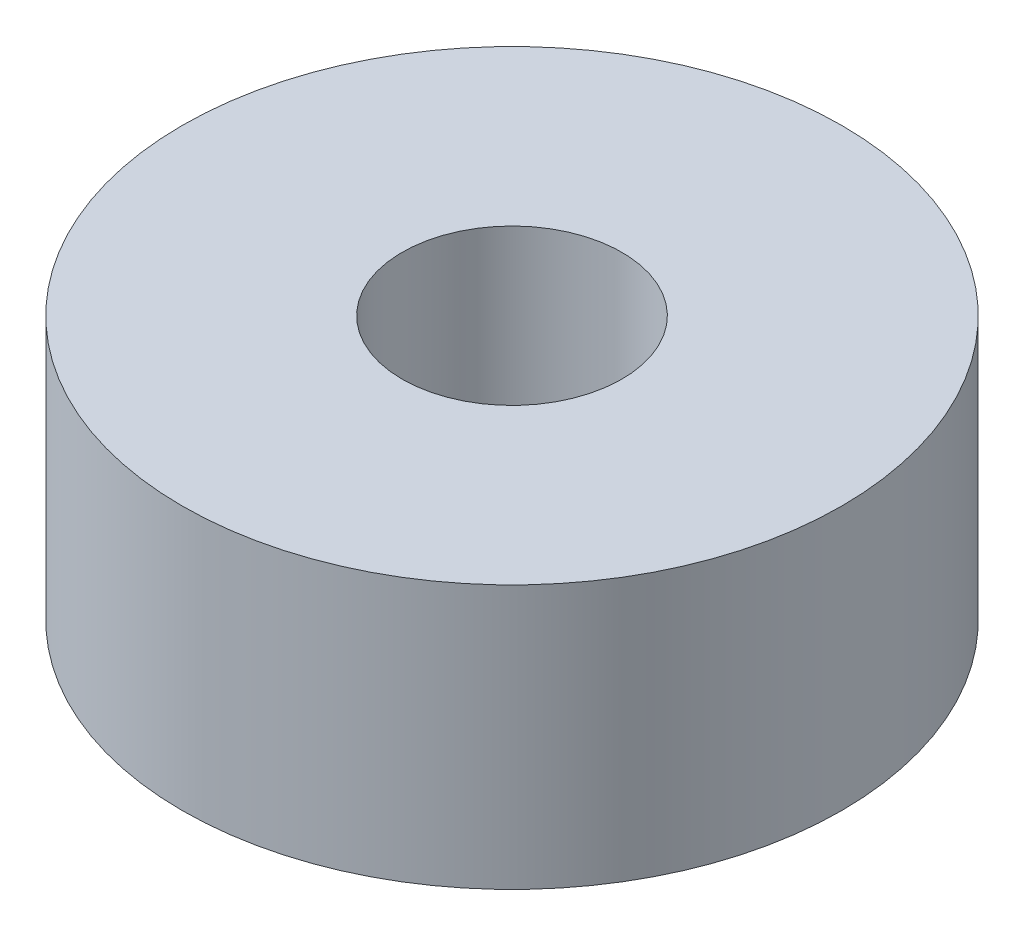
SolidWorks part; units mm, degrees
ref_plane "Płaszczyzna przednia" through (0, 0, 0) normal (0, 0, 1) x (1, 0, 0)
ref_plane "Płaszczyzna górna" through (0, 0, 0) normal (0, 1, 0) x (1, 0, 0)
ref_plane "Płaszczyzna prawa" through (0, 0, 0) normal (1, 0, 0) x (0, 0, -1)
sketch "Szkic1" plane through (0, 0, 0) normal (0, 1, 0) x (1, 0, 0)
  circle A0 centre (0, 0) radius 2.5
  circle A1 centre (0, 0) radius 7.5
  dimension "D1" = 15
  dimension "D2" = 5
extrude "Dodanie-wyciągnięcie1" add sketch "Szkic1" along normal blind 6
